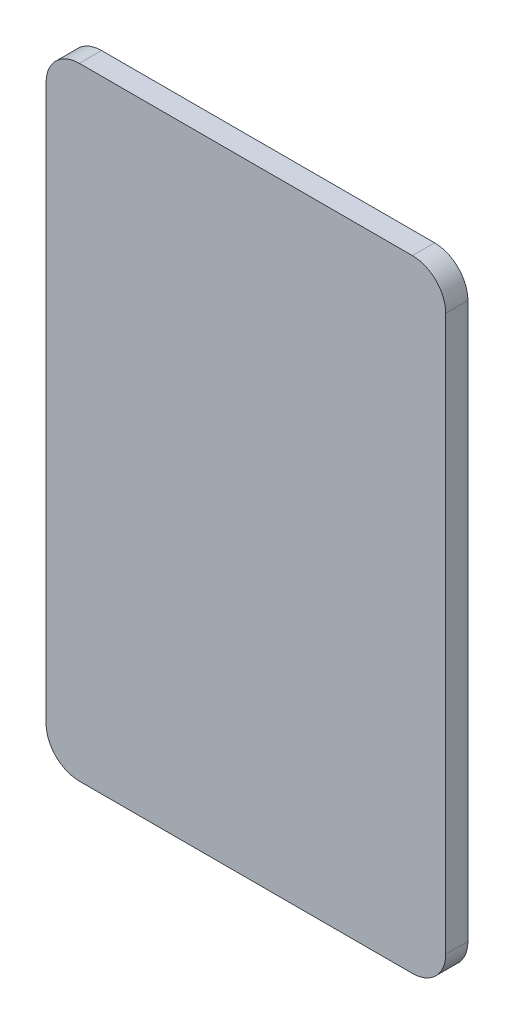
SolidWorks part; units mm, degrees
ref_plane "Front Plane" through (0, 0, 0) normal (0, 0, 1) x (1, 0, 0)
ref_plane "Top Plane" through (0, 0, 0) normal (0, 1, 0) x (1, 0, 0)
ref_plane "Right Plane" through (0, 0, 0) normal (1, 0, 0) x (0, 0, -1)
sketch "Sketch1" plane through (0, 0, 0) normal (0, 0, 1) x (1, 0, 0)
  line L1 (-150, -280) -> (150, -280)
  line L2 (-180, -250) -> (-180, 250)
  line L3 (-150, 280) -> (150, 280)
  line L4 (180, -250) -> (180, 250)
  line L5 (-180, -280) -> (180, 280) construction
  line L6 (-180, 280) -> (180, -280) construction
  arc A0 (-150, -280) -> (-180, -250) centre (-150, -250) cw
  arc A1 (150, -280) -> (180, -250) centre (150, -250) ccw
  arc A2 (150, 280) -> (180, 250) centre (150, 250) cw
  arc A3 (-180, 250) -> (-150, 280) centre (-150, 250) cw
  point P0 (0, 0)
  dimension "D1" = 30
  dimension "D2" = 300
  dimension "D3" = 500
extrude "Boss-Extrude1" add sketch "Sketch1" along normal blind 20
